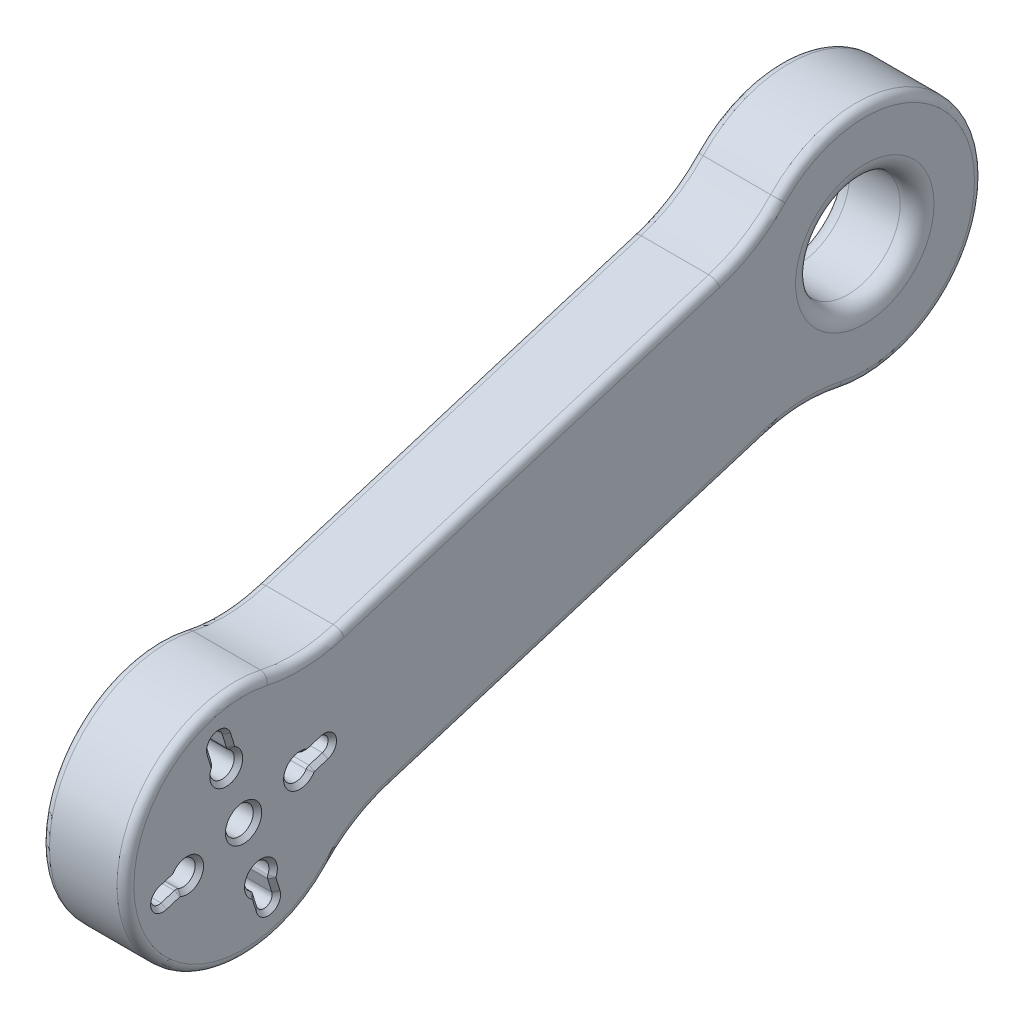
SolidWorks part; units mm, degrees
material "ABS"
ref_plane "Front Plane" through (0, 0, 0) normal (1, 0, 0) x (0, 1, 0)
ref_plane "Top Plane" through (0, 0, 0) normal (0, 0, 1) x (0, 1, 0)
ref_plane "Right Plane" through (0, 0, 0) normal (0, 1, 0) x (-1, 0, 0)
sketch "Sketch1" plane through (0, 0, 0) normal (1, 0, 0) x (0, 1, 0)
  line L0 (-11.6048, -20) -> (24.9519, -20)
  line L1 (84.9519, 40) -> (84.9519, 57.8005)
  line L4 (-38.5328, 56.8878) -> (-47.7982, 43.6554)
  line L5 (64.9519, 37.5) -> (87.5414, -36.1119)
  line L6 (87.5414, -36.1119) -> (67.3498, -81.8536)
  line L7 (67.3498, -81.8536) -> (4.2234, -204.9062)
  line L8 (67.3498, -81.8536) -> (0, 0)
  line L9 (0, 0) -> (64.9519, 37.5) construction
  line L11 (-49.5322, 36.7009) -> (-46.3439, 10.7346)
  line L12 (-32.0778, 61.0001) -> (61.4789, 77.4967)
  arc A0 (24.9519, -20) -> (84.9519, 40) centre (24.9519, 40) ccw
  arc A1 (84.9519, 57.8005) -> (61.4789, 77.4967) centre (64.9519, 57.8005) ccw
  circle A3 centre (0, 0) radius 5
  circle A4 centre (0, 0) radius 10
  circle A5 centre (64.9519, 37.5) radius 5
  circle A6 centre (64.9519, 37.5) radius 10
  circle A7 centre (87.5414, -36.1119) radius 5
  circle A8 centre (87.5414, -36.1119) radius 10
  circle A9 centre (67.3498, -81.8536) radius 5
  circle A10 centre (67.3498, -81.8536) radius 10
  circle A11 centre (4.2234, -204.9062) radius 10
  circle A12 centre (4.2234, -204.9062) radius 50
  arc A13 (-46.3439, 10.7346) -> (-11.6048, -20) centre (-11.6048, 15) ccw
  arc A14 (-47.7982, 43.6554) -> (-49.5322, 36.7009) centre (-39.6067, 37.9196) ccw
  arc A16 (-32.0778, 61.0001) -> (-38.5328, 56.8878) centre (-30.3413, 51.152) ccw
  dimension "D3" = 60
  dimension "D16" = 20
  dimension "D17" = 10
  dimension "D18" = 20
  dimension "D19" = 100
  dimension "D22" = 35
  dimension "D24" = 10
  dimension "D7" = 10
  dimension "D1" = 20
  dimension "D4" = 20
  dimension "D5" = 95
  dimension "D9" = 10
  dimension "D10" = 75
  dimension "D11" = 77
  dimension "D12" = 50
  dimension "D13" = 138.3
  dimension "D14" = 3.34
  dimension "D15" = 30
  dimension "D20" = 106
sketch "Sketch3" plane through (0, 0, 0) normal (1, 0, 0) x (0, 1, 0)
  line L1 (73.5129, -24.4843) -> (59.8604, 20.005)
  line L2 (78.9804, 25.8724) -> (92.6329, -18.6169)
  line L3 (64.9519, 37.5) -> (87.5414, -36.1119) construction
  line L4 (58.2599, 35.4464) -> (71.6439, 39.5536) construction
  line L5 (62.8983, 44.192) -> (67.0055, 30.808) construction
  line L6 (66.9774, 27.6613) -> (66.4909, 29.2467)
  line L7 (68.7938, 28.2187) -> (68.3073, 29.8041)
  line L8 (68.7938, 28.2187) -> (66.9774, 27.6613) construction
  line L9 (55.6706, 33.6581) -> (57.256, 34.1446)
  line L10 (55.1132, 35.4745) -> (56.6986, 35.961)
  line L11 (61.11, 46.7813) -> (61.5965, 45.1959)
  line L12 (62.9264, 47.3387) -> (63.4129, 45.7533)
  line L13 (74.2332, 41.3419) -> (72.6478, 40.8554)
  line L14 (74.7906, 39.5255) -> (73.2052, 39.039)
  arc A0 (78.6269, 34.5011) -> (55.3129, 27.3467) centre (64.9519, 37.5) ccw
  arc A1 (73.8663, -33.1131) -> (97.1804, -25.9586) centre (87.5414, -36.1119) ccw
  circle A2 centre (87.5414, -36.1119) radius 10 construction
  arc A3 (78.6269, 34.5011) -> (78.9804, 25.8724) centre (95.2324, 30.8596) ccw
  circle A5 centre (87.5414, -36.1119) radius 6.2
  circle A6 centre (87.5414, -36.1119) radius 10 construction
  circle A7 centre (64.9519, 37.5) radius 10 construction
  arc A9 (92.6329, -18.6169) -> (97.1804, -25.9586) centre (108.8849, -13.6296) ccw
  arc A10 (73.5129, -24.4843) -> (73.8663, -33.1131) centre (57.2609, -29.4716) cw
  arc A11 (55.3129, 27.3467) -> (59.8604, 20.005) centre (43.6084, 15.0177) cw
  circle A12 centre (64.9519, 37.5) radius 7 construction
  arc A13 (61.5718, 44.7776) -> (63.668, 45.4208) centre (62.8983, 44.192) ccw
  arc A14 (72.2295, 40.8801) -> (72.8727, 38.7839) centre (71.6439, 39.5536) ccw
  arc A15 (68.332, 30.2224) -> (66.2358, 29.5792) centre (67.0055, 30.808) ccw
  arc A16 (57.6743, 34.1199) -> (57.0311, 36.2161) centre (58.2599, 35.4464) ccw
  circle A17 centre (64.9519, 37.5) radius 1.65
  arc A19 (66.9774, 27.6613) -> (68.7938, 28.2187) centre (67.8856, 27.94) ccw
  arc A20 (68.332, 30.2224) -> (68.3073, 29.8041) centre (68.8809, 29.9801) ccw
  arc A21 (66.4909, 29.2467) -> (66.2358, 29.5792) centre (65.9173, 29.0707) ccw
  arc A22 (57.6743, 34.1199) -> (57.256, 34.1446) centre (57.432, 33.571) ccw
  arc A23 (56.6986, 35.961) -> (57.0311, 36.2161) centre (56.5226, 36.5346) ccw
  arc A24 (55.1132, 35.4745) -> (55.6706, 33.6581) centre (55.3919, 34.5663) ccw
  arc A25 (61.5718, 44.7776) -> (61.5965, 45.1959) centre (61.0229, 45.0199) ccw
  arc A26 (63.4129, 45.7533) -> (63.668, 45.4208) centre (63.9865, 45.9293) ccw
  arc A27 (62.9264, 47.3387) -> (61.11, 46.7813) centre (62.0182, 47.06) ccw
  arc A28 (72.2295, 40.8801) -> (72.6478, 40.8554) centre (72.4718, 41.429) ccw
  arc A29 (73.2052, 39.039) -> (72.8727, 38.7839) centre (73.3812, 38.4654) ccw
  arc A30 (74.7906, 39.5255) -> (74.2332, 41.3419) centre (74.5119, 40.4337) ccw
  dimension "D1" = 10
  dimension "D2" = 77
  dimension "D3" = 12.4
  dimension "D4" = 28
  dimension "D5" = 17
  dimension "D6" = 2.9
  dimension "D7" = 3.3
  dimension "D8" = 14
  dimension "D9" = 1.9
  dimension "D10" = 3
  dimension "D11" = 0.6
  dimension "D12" = 4
extrude "Boss-Extrude2" add sketch "Sketch3" along normal blind 10
fillet "Fillet2" radius 1 16 edges at (0, 66.6867, -2.2397) (10, 66.6867, -2.2397) (0, 60.8447, 50.884) (0, 58.0606, 23.9694) (0, 74.2467, -28.7758) (0, 91.6486, -49.4959) (0, 94.4327, -22.5813) (0, 85.8066, 3.6277) (0, 78.2466, 30.1639) (10, 85.8066, 3.6277) (10, 94.4327, -22.5813) (10, 91.6486, -49.4959) (10, 74.2467, -28.7758) (10, 58.0606, 23.9694) (10, 60.8447, 50.884) (10, 78.2466, 30.1639)
fillet "Fillet3" radius 2 2 edges at (0, 87.5414, -42.3119) (10, 87.5414, -42.3119)
chamfer "Chamfer1" distance 0.5 angle 45 50 edges at (0, 63.3237, 42.8058) (10, 63.3237, 42.8058) (0, 70.2577, 39.1282) (10, 70.2577, 39.1282) (0, 64.9519, 35.85) (10, 64.9519, 35.85) (0, 59.6461, 35.8718) (10, 59.6461, 35.8718) (0, 66.5801, 32.1942) (10, 66.5801, 32.1942) (10, 61.3533, 45.9886) (10, 61.6219, 44.9845) (10, 61.7395, 47.9682) (10, 63.1697, 46.546) (10, 63.5105, 45.5641) (0, 61.3533, 45.9886) (0, 61.6219, 44.9845) (0, 61.7395, 47.9682) (0, 63.1697, 46.546) (0, 63.5105, 45.5641) (10, 72.4364, 40.83) (10, 73.4405, 41.0986) (10, 75.4201, 40.7124) (10, 73.9979, 39.2822) (10, 73.016, 38.9414) (0, 72.4364, 40.83) (0, 73.4405, 41.0986) (0, 75.4201, 40.7124) (0, 73.9979, 39.2822) (0, 73.016, 38.9414) (10, 55.9059, 35.7178) (10, 56.8878, 36.0586) (10, 54.4837, 34.2876) (10, 56.4633, 33.9014) (10, 57.4674, 34.17) (0, 55.9059, 35.7178) (0, 56.8878, 36.0586) (0, 54.4837, 34.2876) (0, 56.4633, 33.9014) (0, 57.4674, 34.17) (10, 66.3933, 29.4359) (10, 66.7341, 28.454) (10, 68.1643, 27.0318) (10, 68.5505, 29.0114) (10, 68.2819, 30.0155) (0, 66.3933, 29.4359) (0, 66.7341, 28.454) (0, 68.1643, 27.0318) (0, 68.5505, 29.0114) (0, 68.2819, 30.0155)
